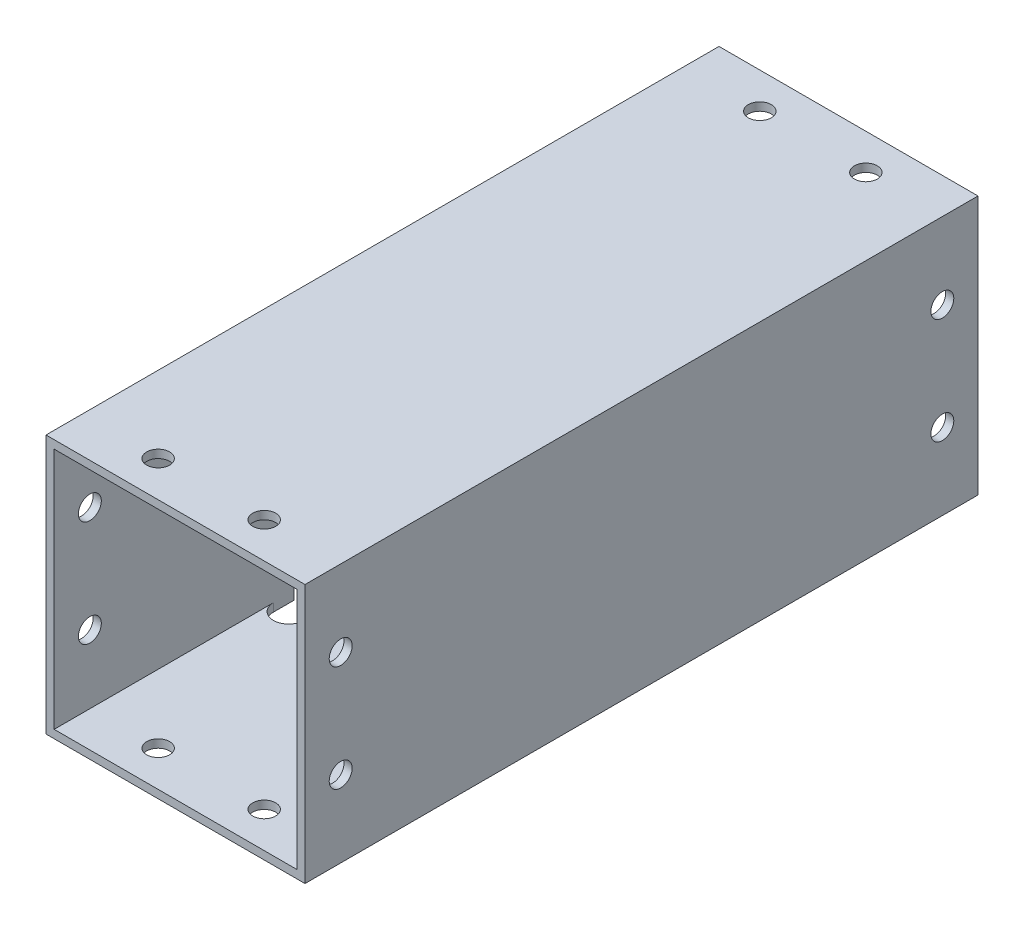
SolidWorks part; units mm, degrees
ref_plane "Front Plane" through (0, 0, 0) normal (0, 0, 1) x (1, 0, 0)
ref_plane "Top Plane" through (0, 0, 0) normal (0, 1, 0) x (1, 0, 0)
ref_plane "Right Plane" through (0, 0, 0) normal (1, 0, 0) x (0, 0, -1)
sketch "Sketch1" plane through (0, 0, 0) normal (0, 0, 1) x (1, 0, 0)
  line L0 (-23.8, 23.8) -> (23.8, 23.8)
  line L1 (-25.4, -25.4) -> (25.4, -25.4)
  line L2 (-25.4, -25.4) -> (-25.4, 25.4)
  line L3 (-25.4, 25.4) -> (25.4, 25.4)
  line L4 (25.4, -25.4) -> (25.4, 25.4)
  line L5 (-25.4, -25.4) -> (25.4, 25.4) construction
  line L6 (-25.4, 25.4) -> (25.4, -25.4) construction
  line L7 (23.8, -23.8) -> (23.8, 23.8)
  line L8 (-23.8, -23.8) -> (23.8, -23.8)
  line L9 (-23.8, -23.8) -> (-23.8, 23.8)
  point P0 (0, 0)
  dimension "D1" = 50.8
  dimension "D2" = 50.8
  dimension "D3" = 1.6
extrude "Boss-Extrude1" add sketch "Sketch1" along normal blind 132
sketch "Sketch2" plane through (0, 0, 0) normal (0, 0, 1) x (1, 0, 0)
  point P0 (0, 0)
sketch "Sketch3" plane through (0, 0, 0) normal (1, 0, 0) x (0, 0, -1)
  line L0 (0, 0) -> (-143.944, 0) construction
ref_plane "Plane1" through (0, 0, 66) normal (0, 0, 1) x (1, 0, 0)
hole_wizard "M4 Clearance Hole1" positions "Sketch4" profile "Sketch5" hole size "M4" standard "ISO"
sketch "Sketch4" plane through (-25.4, 0, 0) normal (-1, 0, 0) x (0, 0, 1)
  line L0 (132, 25.4) -> (0, 25.4) construction
  point P0 (7, 10.4)
  point P2 (7, -10.4)
  dimension "D1" = 15
  dimension "D2" = 7
  dimension "D3" = 15
  dimension "D4" = 7
sketch "Sketch5" plane through (-25.4, 10.4, 7) normal (0, 1, 0) x (0, 0, 1)
  line L0 (0, 0) -> (0, 12.8519)
  line L1 (0, 12.8519) -> (2.25, 11.5)
  line L2 (2.25, 11.5) -> (2.25, 0)
  line L5 (2.25, 0) -> (0, 0)
  line L10 (0, 12.8519) -> (-2.25, 11.5) construction
  line L11 (0, -6.35) -> (0, 107.95) construction
  dimension "Hole Dia." = 4.5
  dimension "Hole Depth" = 11.5
  dimension "Drill Angle" = 118
sketch "Sketch6" plane through (0, 0, 0) normal (1, 0, 0) x (0, 0, -1)
  line L0 (0, 0) -> (-139.4385, 0) construction
pattern_circular "CirPattern1" count 4 every 90 about axis through (0, 0, 0) along (0, 0, 1) of "M4 Clearance Hole1"
mirror "Mirror3" about plane through (0, 0, 66) normal (0, 0, 1) of "CirPattern1", "M4 Clearance Hole1"
sketch "Sketch7" plane through (-25.4, 0, 0) normal (-1, 0, 0) x (0, 0, 1)
  line L0 (82, -15.1) -> (82, -30.1) construction
  line L1 (85, -15.1) -> (85, -30.1)
  line L2 (79, -15.1) -> (79, -30.1)
  line L3 (132, 25.4) -> (0, 25.4) construction
  arc A0 (85, -15.1) -> (79, -15.1) centre (82, -15.1) ccw
  arc A1 (79, -30.1) -> (85, -30.1) centre (82, -30.1) ccw
  point P2 (82, -22.6)
  dimension "D1" = 48
  dimension "D2" = 3
  dimension "D3" = 15
  dimension "D4" = 50
extrude "Cut-Extrude1" cut sketch "Sketch7" against normal blind 5
sketch "Sketch8" plane through (0, -25.4, 0) normal (0, -1, 0) x (1, 0, 0)
  line L0 (-20.8, 75) -> (-20.8, 89) construction
  line L1 (-23.8, 75) -> (-23.8, 89)
  line L2 (-17.8, 75) -> (-17.8, 89)
  line L3 (-23.8, 79) -> (-23.8, 85) construction
  arc A0 (-23.8, 75) -> (-17.8, 75) centre (-20.8, 75) ccw
  arc A1 (-17.8, 89) -> (-23.8, 89) centre (-20.8, 89) ccw
  point P2 (-20.8, 82)
  dimension "D2" = 3
  dimension "D1" = 3
  dimension "D3" = 3
  dimension "D4" = 14
extrude "Cut-Extrude2" cut sketch "Sketch8" against normal blind 10
